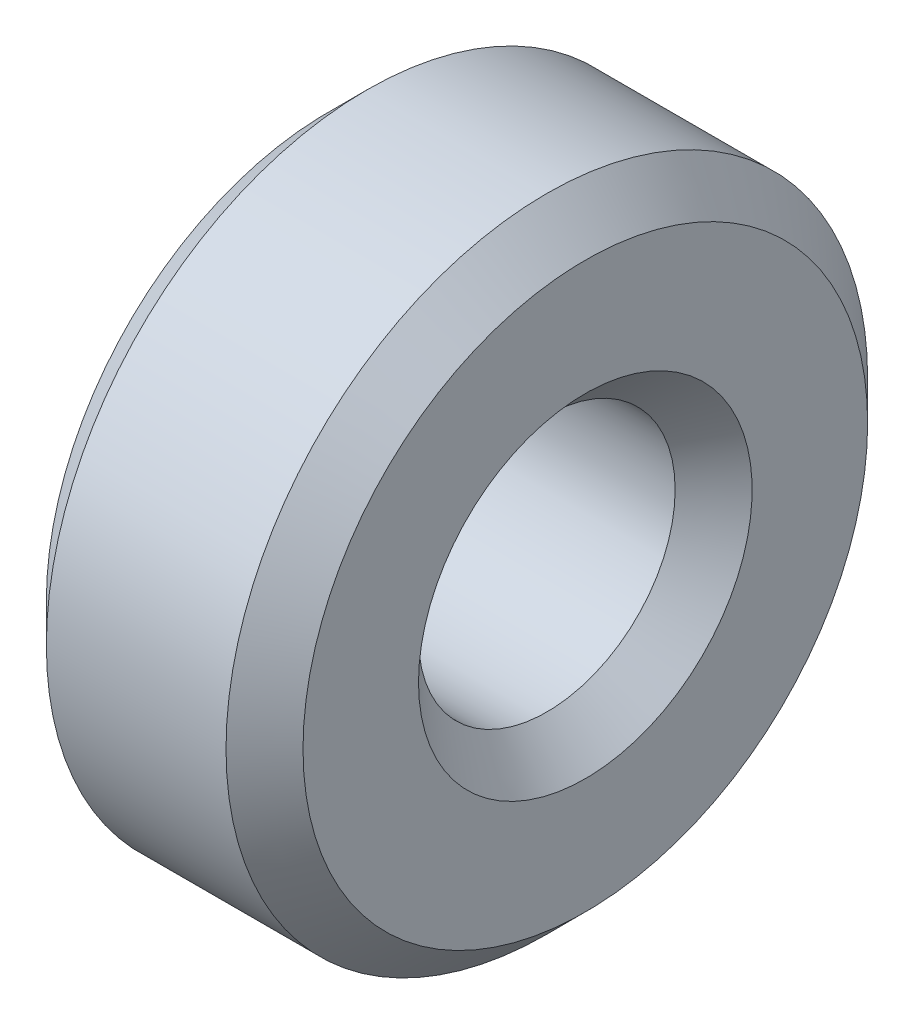
SolidWorks part; units mm, degrees
ref_plane "Přední rovina" through (0, 0, 0) normal (0, 0, 1) x (1, 0, 0)
ref_plane "Vrchní rovina" through (0, 0, 0) normal (0, 1, 0) x (1, 0, 0)
ref_plane "Pravá rovina" through (0, 0, 0) normal (1, 0, 0) x (0, 0, -1)
sketch "Skica1" plane through (0, 0, 0) normal (0, 0, 1) x (1, 0, 0)
  line L0 (0, 0) -> (2, 0) construction
  line L1 (0, 1) -> (0, 2.5)
  line L2 (0, 2.5) -> (2, 2.5)
  line L3 (2, 2.5) -> (2, 1)
  line L4 (0, 1) -> (2, 1)
  dimension "D1" = 2
  dimension "B1" = 2
  dimension "D2" = 5
revolve "Otočit kolem osy1" add sketch "Skica1" angle 360 about L0
chamfer "Zkosit1" distance 0.3 angle 45 4 edges at (0, 0, 2.5) (0, 0, 1) (2, 0, 1) (2, 0, 2.5)
